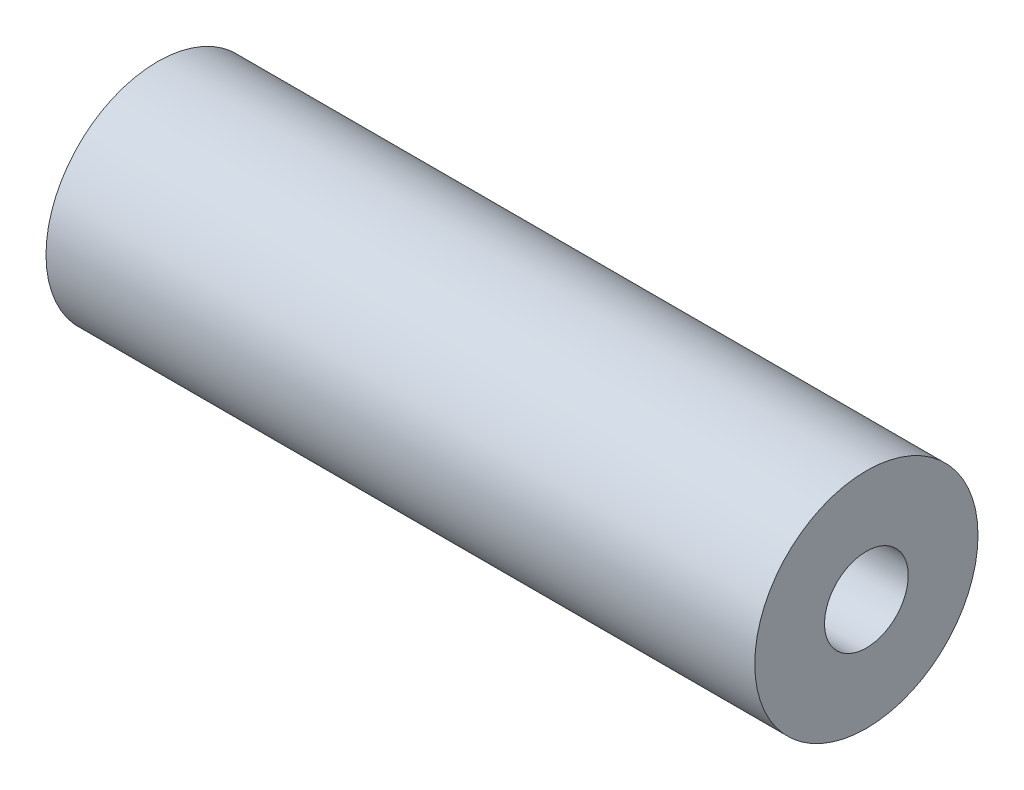
SolidWorks part; units mm, degrees
material "1060 合金"
ref_plane "正面" through (0, 0, 0) normal (0, 0, 1) x (1, 0, 0)
ref_plane "平面" through (0, 0, 0) normal (0, 1, 0) x (1, 0, 0)
ref_plane "右側面" through (0, 0, 0) normal (1, 0, 0) x (0, 0, -1)
sketch "ｽｹｯﾁ1" plane through (0, 0, 0) normal (1, 0, 0) x (0, 0, -1)
  circle A0 centre (0, 0) radius 4
  circle A1 centre (0, 0) radius 1.5
  dimension "D1" = 8
  dimension "D2" = 3
extrude "ﾎﾞｽ - 押し出し1" add sketch "ｽｹｯﾁ1" along normal blind 25.4
